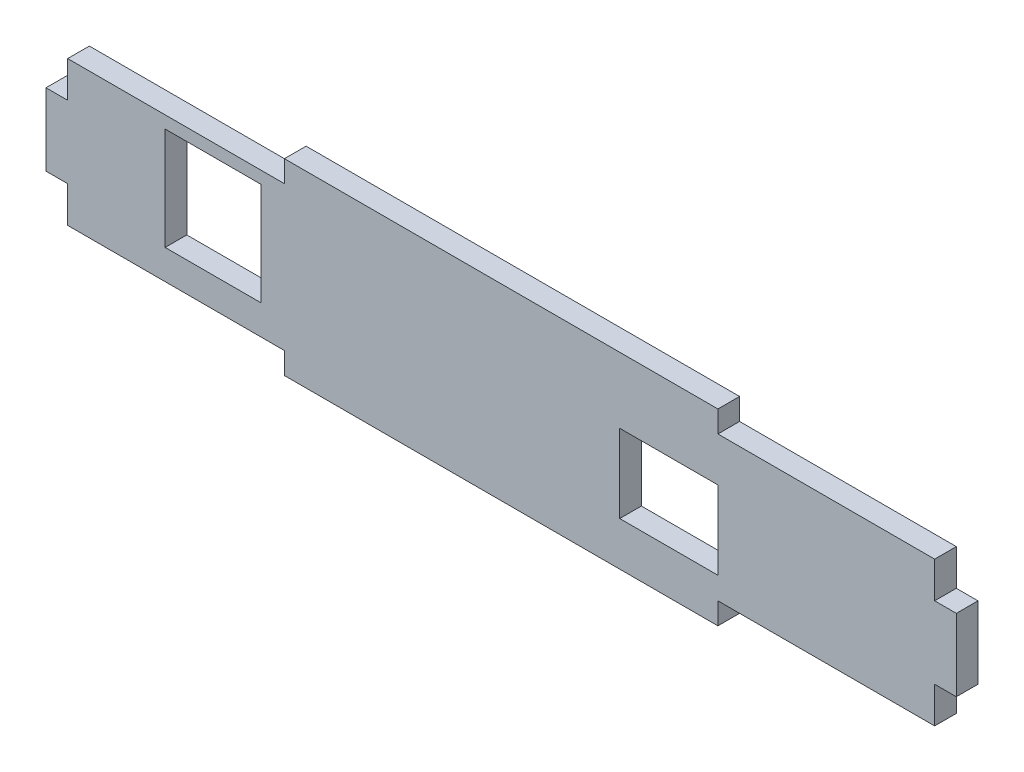
SolidWorks part; units mm, degrees
ref_plane "Front Plane" through (0, 0, 0) normal (0, 0, 1) x (1, 0, 0)
ref_plane "Top Plane" through (0, 0, 0) normal (0, 1, 0) x (1, 0, 0)
ref_plane "Right Plane" through (0, 0, 0) normal (1, 0, 0) x (0, 0, -1)
sketch "Sketch1" plane through (0, 0, 0) normal (0, 0, 1) x (1, 0, 0)
  line L0 (0, 10) -> (-1.5, 10) construction
  line L1 (0, 0) -> (120, 0) construction
  line L2 (0, 0) -> (0, 20) construction
  line L3 (0, 20) -> (120, 20) construction
  line L4 (120, 0) -> (120, 20) construction
  line L5 (60, 20) -> (60, 21.5) construction
  line L6 (60, 0) -> (60, -1.5) construction
  line L7 (120, 10) -> (121.5, 10) construction
  line L8 (0, 0) -> (0, 5)
  line L9 (-3, 15) -> (0, 15) construction
  line L10 (-3, 15) -> (-3, 5) construction
  line L11 (-3, 5) -> (0, 5) construction
  line L12 (0, 15) -> (0, 5) construction
  line L13 (-3, 15) -> (0, 5) construction
  line L14 (-3, 5) -> (0, 15) construction
  line L15 (30, 23) -> (90, 23) construction
  line L16 (30, 23) -> (30, 20) construction
  line L17 (30, 20) -> (90, 20) construction
  line L18 (90, 23) -> (90, 20) construction
  line L19 (30, 23) -> (90, 20) construction
  line L20 (30, 20) -> (90, 23) construction
  line L21 (123, 15) -> (120, 15) construction
  line L22 (123, 15) -> (123, 5) construction
  line L23 (123, 5) -> (120, 5) construction
  line L24 (120, 15) -> (120, 5) construction
  line L25 (123, 15) -> (120, 5) construction
  line L26 (123, 5) -> (120, 15) construction
  line L27 (30, -3) -> (90, -3) construction
  line L28 (30, -3) -> (30, 0) construction
  line L29 (30, 0) -> (90, 0) construction
  line L30 (90, -3) -> (90, 0) construction
  line L31 (30, -3) -> (90, 0) construction
  line L32 (30, 0) -> (90, -3) construction
  line L33 (0, 5) -> (-3, 5)
  line L34 (-3, 5) -> (-3, 15)
  line L35 (-3, 15) -> (0, 15)
  line L36 (0, 15) -> (0, 20)
  line L37 (0, 20) -> (30, 20)
  line L38 (30, 20) -> (30, 23)
  line L39 (30, 23) -> (90, 23)
  line L40 (90, 23) -> (90, 20)
  line L41 (90, 20) -> (120, 20)
  line L42 (120, 20) -> (120, 15)
  line L43 (120, 15) -> (123, 15)
  line L44 (123, 15) -> (123, 5)
  line L45 (123, 5) -> (120, 5)
  line L46 (120, 5) -> (120, 0)
  line L47 (120, 0) -> (90, 0)
  line L48 (90, 0) -> (90, -3)
  line L49 (90, -3) -> (30, -3)
  line L50 (30, -3) -> (30, 0)
  line L51 (30, 0) -> (0, 0)
  line L53 (26.7516, 18.2997) -> (13.49, 18.2997)
  line L54 (26.7516, 18.2997) -> (26.7516, 4.1025)
  line L55 (26.7516, 4.1025) -> (13.49, 4.1025)
  line L56 (13.49, 18.2997) -> (13.49, 4.1025)
  line L57 (90, 13.8881) -> (76.4101, 13.8881)
  line L58 (90, 13.8881) -> (90, 3.0666)
  line L59 (90, 3.0666) -> (76.4101, 3.0666)
  line L60 (76.4101, 13.8881) -> (76.4101, 3.0666)
extrude "Boss-Extrude1" add sketch "Sketch1" along normal blind 3
